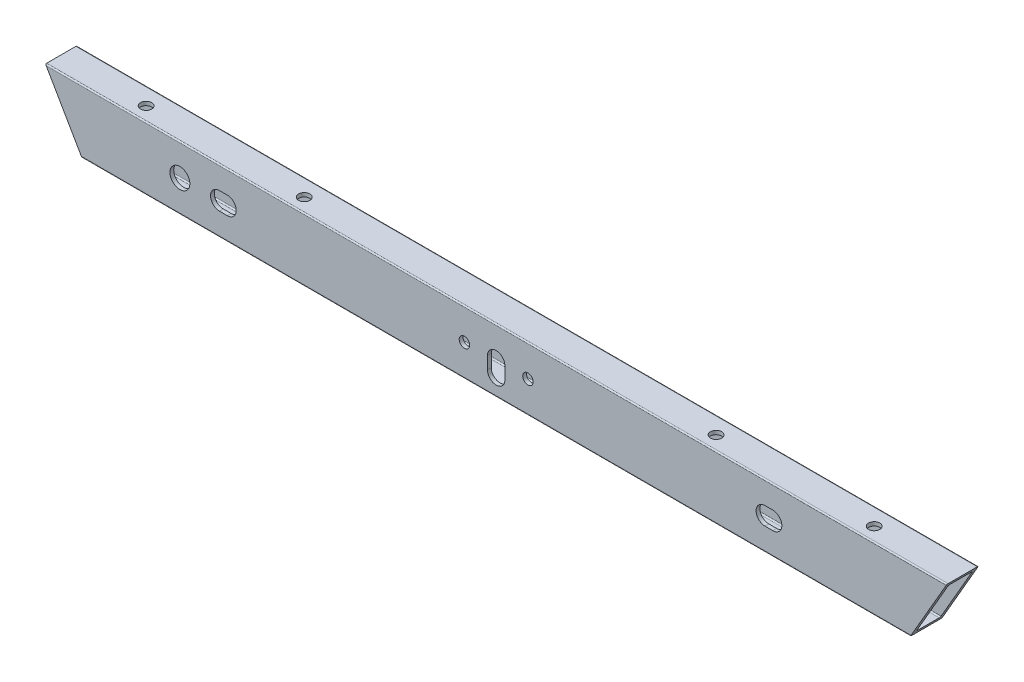
SolidWorks part; units mm, degrees
ref_plane "Front Plane" through (0, 0, 0) normal (0, 0, 1) x (1, 0, 0)
ref_plane "Top Plane" through (0, 0, 0) normal (0, 1, 0) x (1, 0, 0)
ref_plane "Right Plane" through (0, 0, 0) normal (1, 0, 0) x (0, 0, -1)
sketch "Sketch2" plane through (0, 0, 0) normal (0, 0, 1) x (1, 0, 0)
  line L0 (-332.6206, -25.4) -> (-361.95, 25.4)
  line L1 (-361.95, 25.4) -> (361.95, 25.4)
  line L3 (-332.6206, -25.4) -> (332.6206, -25.4)
  line L5 (0, 25.4) -> (0, -25.4) construction
  line L8 (332.6206, -25.4) -> (361.95, 25.4)
  point P0 (0, 0)
  point P4 (0, 0)
  point P8 (0, 25.4)
  dimension "D1" = 50.8
  dimension "D2" = 60
  dimension "D3" = 723.9
extrude "Boss-Extrude1" add sketch "Sketch2" along normal mid plane 25.4 contours L1 L8 L3 L0
sketch "Sketch3" plane through (0, 0, 0) normal (1, 0, 0) x (0, 0, -1)
  line L12 (9.652, -22.352) -> (9.652, 22.352)
  line L13 (-9.652, -22.352) -> (9.652, -22.352)
  line L14 (-9.652, 22.352) -> (-9.652, -22.352)
  line L15 (9.652, 22.352) -> (-9.652, 22.352)
  line L16 (9.652, -22.352) -> (9.652, 22.352)
  line L17 (-9.652, -22.352) -> (9.652, -22.352)
  line L18 (-9.652, 22.352) -> (-9.652, -22.352)
  line L19 (9.652, 22.352) -> (-9.652, 22.352)
  dimension "D1" = 3.048
extrude "Cut-Extrude1" cut sketch "Sketch3" against normal through all and the other way through all contours L16 L19 L18 L17
fillet "Fillet1" radius 1 8 edges at (0, 22.352, 9.652) (0, 22.352, -9.652) (0, -22.352, -9.652) (0, -22.352, 9.652) (0, -25.4, -12.7) (0, -25.4, 12.7) (0, 25.4, -12.7) (0, 25.4, 12.7)
sketch "Sketch4" plane through (0, 0, -12.7) normal (0, 0, -1) x (-1, 0, 0)
  line L1 (-7, 0) -> (-7, -10)
  line L2 (7, 0) -> (7, -10)
  arc A0 (7, 0) -> (-7, 0) centre (0, 0) ccw
  arc A1 (-7, -10) -> (7, -10) centre (0, -10) ccw
  dimension "D1" = 14
  dimension "D2" = 10
extrude "WireHole" cut sketch "Sketch4" against normal up to next
sketch "Sketch5" plane through (0, 0, 12.7) normal (0, 0, 1) x (1, 0, 0)
  circle A12 centre (0, 0) radius 15
  arc A13 (8.7312, 0) -> (-8.7312, 0) centre (0, 0) ccw construction
  dimension "D1" = 30
extrude "MiddleHole" cut sketch "Sketch5" against normal up to next
hole_wizard "SpacerHolesM8" positions "Sketch42" profile "Sketch41" hole size "M8" standard "ANSI Metric" end condition through all
sketch "Sketch42" [suppressed] plane through (0, 0, 12.7) normal (0, 0, 1) x (1, 0, 0)
  circle A3 centre (25.5, 0) radius 3.5 construction
  circle A4 centre (-25.5, 0) radius 3.5 construction
  point P0 (-25.5, 0)
  point P2 (25.5, 0)
sketch "Sketch41" plane through (-25.5, 0, 12.7) normal (1, 0, 0) x (0, -1, 0)
  line L0 (0, 0) -> (0, 25.4)
  line L1 (0, 25.4) -> (4.2, 25.4)
  line L2 (4.2, 25.4) -> (4.2, 0)
  line L5 (4.2, 0) -> (0, 0)
  line L11 (0, -6.35) -> (0, 107.95) construction
  dimension "Thru Hole Dia." = 8.4
  dimension "Thru Hole Depth" = 25.4
sketch "Sketch9" plane through (0, 0, -12.7) normal (0, 0, -1) x (-1, 0, 0)
  line L0 (-222.25, 0) -> (-215.9, 0) construction
  line L1 (-222.25, 7.1437) -> (-215.9, 7.1437)
  line L2 (-222.25, -7.1437) -> (-215.9, -7.1437)
  line L3 (0, 13.97) -> (0, -13.97) construction
  line L4 (222.25, 0) -> (215.9, 0) construction
  line L5 (222.25, 7.1437) -> (215.9, 7.1437)
  line L6 (222.25, -7.1437) -> (215.9, -7.1437)
  arc A0 (-222.25, 7.1437) -> (-222.25, -7.1437) centre (-222.25, 0) ccw
  arc A1 (-215.9, -7.1437) -> (-215.9, 7.1437) centre (-215.9, 0) ccw
  arc A2 (222.25, 7.1437) -> (222.25, -7.1437) centre (222.25, 0) cw
  arc A3 (215.9, -7.1437) -> (215.9, 7.1437) centre (215.9, 0) cw
  point P2 (-219.075, 0)
  point P12 (219.075, 0)
  dimension "D2" = 14.2875
  dimension "D1" = 6.35
  dimension "D3" = 215.9
extrude "Wire Slots" cut sketch "Sketch9" against normal up to next
sketch "Sketch14" plane through (0, 25.4, 0) normal (0, 1, 0) x (1, 0, 0)
  line L0 (-165.35, 1.475) -> (-292.35, 1.475) construction
  line L1 (165.35, 1.475) -> (292.35, 1.475) construction
  line L4 (0, 0) -> (0, 11.7) construction
  line L5 (361.95, 11.7) -> (-361.95, 11.7) construction
  circle A0 centre (-165.35, 1.475) radius 4.5
  circle A2 centre (-292.35, 1.475) radius 4.5
  circle A8 centre (-165.35, 1.475) radius 3.3 construction
  circle A9 centre (-292.35, 1.475) radius 3.3 construction
  circle A10 centre (292.35, 1.475) radius 4.5
  circle A11 centre (165.35, 1.475) radius 4.5
  dimension "D1" = 9
  dimension "D2" = 165.3566
  dimension "D3" = 127
extrude "Plate Mounting" cut sketch "Sketch14" against normal up to next
ref_plane "Plane1" through (0, 0, 15.24) normal (0, 0, 1) x (1, 0, 0)
hole_wizard "M6x1.0 Tapped Hole1" positions "Sketch43" profile "Sketch37" tap size "M6x1.0" standard "ANSI Metric"
sketch "Sketch43" [suppressed] plane through (0, 0, 15.24) normal (0, 0, -1) x (-1, 0, 0)
  line L0 (13.97, 0) -> (-13.97, 0) construction
  line L2 (0, 13.97) -> (0, -13.97) construction
  point P0 (-330.2, 0)
  point P4 (330.2, 0)
  dimension "D1" = 660.4
  dimension "D2" = 330.2
sketch "Sketch37" plane through (330.2, 0, 15.24) normal (1, 0, 0) x (0, -1, 0)
  line L0 (0, 0) -> (0, 5.588)
  line L1 (0, 5.588) -> (2.5, 5.588)
  line L2 (2.5, 5.588) -> (2.5, 0)
  line L5 (2.5, 0) -> (0, 0)
  line L11 (0, -6.35) -> (0, 107.95) construction
  dimension "Thru Tap Drill Dia." = 5
  dimension "Thru Tap Drill Depth" = 5.588
mirror "Mirror1" about plane through (0, 0, -12.7) normal (0, 0, -1) of bodies 118 106
sketch "Sketch10" plane through (0, 0, 0) normal (1, 0, 0) x (0, 0, -1)
  line L0 (-12.7, -24.4) -> (-12.7, 24.4) construction
  line L1 (12.7, -25.4) -> (-12.7, -25.4)
  line L2 (12.7, -25.4) -> (12.7, 25.4)
  line L3 (12.7, 25.4) -> (-12.7, 25.4)
  line L4 (-12.7, -25.4) -> (-12.7, 25.4)
  line L5 (12.7, -25.4) -> (-12.7, 25.4) construction
  line L6 (12.7, 25.4) -> (-12.7, -25.4) construction
  line L7 (-11.7, 25.4) -> (11.7, 25.4) construction
  point P0 (0, 0)
extrude "Cut-Extrude5" cut sketch "Sketch10" against normal through all both and the other way through all
sketch "Sketch15" [suppressed] plane through (0, 0, 12.7) normal (0, 0, 1) x (1, 0, 0)
  circle A0 centre (254, 0) radius 11.75
  dimension "D1" = 23.5
  dimension "D2" = 254
extrude "Charging" [suppressed] cut sketch "Sketch15" against normal through all
hole_wizard "ChargingHold" positions "Sketch44" profile "Sketch31" hole size "M4" standard "ANSI Metric"
sketch "Sketch44" [suppressed] plane through (0, 0, 12.7) normal (0, 0, 1) x (1, 0, 0)
  line L1 (244.5, 12) -> (263.5, 12) construction
  line L2 (244.5, 12) -> (244.5, -12) construction
  line L3 (244.5, -12) -> (263.5, -12) construction
  line L4 (263.5, 12) -> (263.5, -12) construction
  line L5 (244.5, 12) -> (263.5, -12) construction
  line L6 (244.5, -12) -> (263.5, 12) construction
  circle A0 centre (254, 0) radius 11.75 construction
  point P0 (244.5, 12)
  point P37 (254, 0)
  dimension "D1" = 19
  dimension "D2" = 24
sketch "Sketch31" plane through (244.5, 12, 12.7) normal (1, 0, 0) x (0, -1, 0)
  line L0 (0, 0) -> (0, 25.4)
  line L1 (0, 25.4) -> (2.25, 25.4)
  line L2 (2.25, 25.4) -> (2.25, 0)
  line L5 (2.25, 0) -> (0, 0)
  line L11 (0, -6.35) -> (0, 107.95) construction
  dimension "Thru Hole Dia." = 4.5
  dimension "Thru Hole Depth" = 25.4
hole_wizard "Power" positions "Sketch45" profile "Sketch18" hole size "M16" standard "ANSI Metric" end condition through all
sketch "Sketch45" plane through (0, 0, -38.1) normal (0, 0, -1) x (-1, 0, 0)
  point P0 (254, 0)
  dimension "D1" = 254
sketch "Sketch18" plane through (-254, 0, -38.1) normal (1, 0, 0) x (0, 1, 0)
  line L0 (0, 0) -> (0, 25.4)
  line L1 (0, 25.4) -> (8, 25.4)
  line L2 (8, 25.4) -> (8, 0)
  line L5 (8, 0) -> (0, 0)
  line L11 (0, -6.35) -> (0, 107.95) construction
  dimension "Thru Hole Dia." = 16
  dimension "Thru Hole Depth" = 25.4
sketch "Sketch23" [suppressed] plane through (0, 0, -12.7) normal (0, 0, 1) x (1, 0, 0)
  line L0 (0, 0) -> (0, 25.0615) construction
  point P0 (330.2, 0)
  point P9 (-330.2, 0)
  dimension "D1" = 330.2
equation "\"Length\"= 28.5"
equation "\"D3@Sketch2\"=\"Length\""
